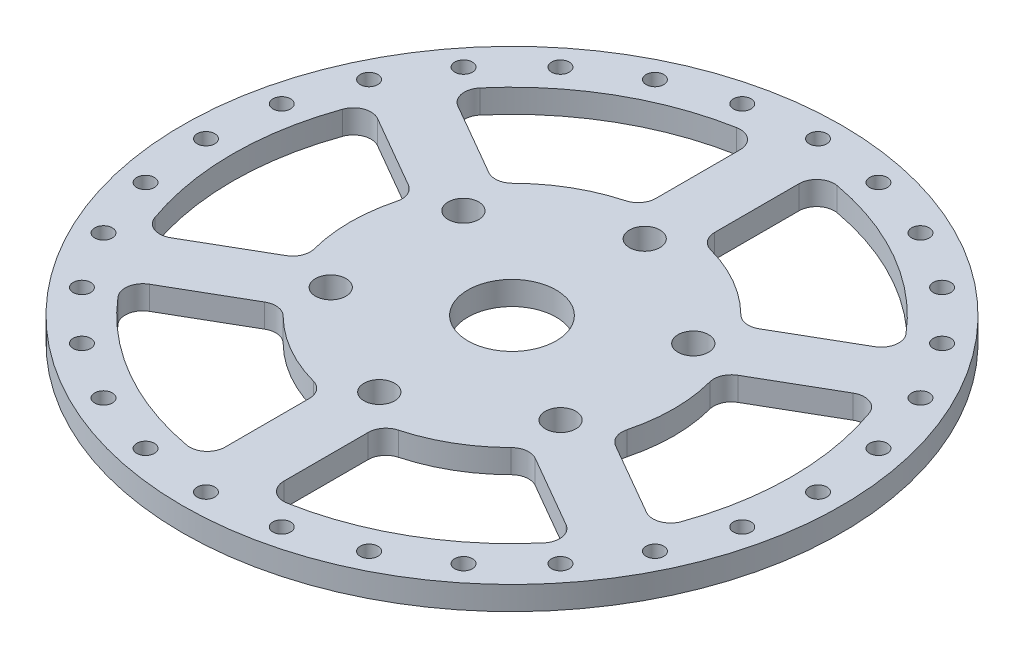
SolidWorks part; units mm, degrees
material "Thornel Mat VMA"
ref_plane "前视基准面" through (0, 0, 0) normal (0, 0, 1) x (1, 0, 0)
ref_plane "上视基准面" through (0, 0, 0) normal (0, 1, 0) x (1, 0, 0)
ref_plane "右视基准面" through (0, 0, 0) normal (1, 0, 0) x (0, 0, -1)
sketch "草图1" plane through (0, 0, 0) normal (0, 1, 0) x (1, 0, 0)
  line L0 (0, 27.5) -> (0, 47.5) construction
  line L1 (-5, 47.2361) -> (-5, 27.0416)
  line L2 (5, 47.2361) -> (5, 27.0416)
  line L3 (38.4077, 27.9482) -> (20.9187, 17.8509)
  line L4 (43.4077, 19.2879) -> (25.9187, 9.1907)
  line L5 (43.4077, -19.2879) -> (25.9187, -9.1907)
  line L6 (38.4077, -27.9482) -> (20.9187, -17.8509)
  line L7 (5, -47.2361) -> (5, -27.0416)
  line L8 (-5, -47.2361) -> (-5, -27.0416)
  line L9 (-38.4077, -27.9482) -> (-20.9187, -17.8509)
  line L10 (-43.4077, -19.2879) -> (-25.9187, -9.1907)
  line L11 (-43.4077, 19.2879) -> (-25.9187, 9.1907)
  line L12 (-38.4077, 27.9482) -> (-20.9187, 17.8509)
  circle A0 centre (0, 0) radius 56
  circle A1 centre (0, 0) radius 52 construction
  circle A2 centre (0, 0) radius 47.5
  circle A3 centre (0, 52) radius 1.5
  circle A4 centre (11.5711, 50.6963) radius 1.5
  circle A5 centre (22.562, 46.8504) radius 1.5
  circle A6 centre (32.4215, 40.6552) radius 1.5
  circle A7 centre (40.6552, 32.4215) radius 1.5
  circle A8 centre (46.8504, 22.562) radius 1.5
  circle A9 centre (50.6963, 11.5711) radius 1.5
  circle A10 centre (52, 0) radius 1.5
  circle A11 centre (50.6963, -11.5711) radius 1.5
  circle A12 centre (46.8504, -22.562) radius 1.5
  circle A13 centre (40.6552, -32.4215) radius 1.5
  circle A14 centre (32.4215, -40.6552) radius 1.5
  circle A15 centre (22.562, -46.8504) radius 1.5
  circle A16 centre (11.5711, -50.6963) radius 1.5
  circle A17 centre (0, -52) radius 1.5
  circle A18 centre (-11.5711, -50.6963) radius 1.5
  circle A19 centre (-22.562, -46.8504) radius 1.5
  circle A20 centre (-32.4215, -40.6552) radius 1.5
  circle A21 centre (-40.6552, -32.4215) radius 1.5
  circle A22 centre (-46.8504, -22.562) radius 1.5
  circle A23 centre (-50.6963, -11.5711) radius 1.5
  circle A24 centre (-52, 0) radius 1.5
  circle A25 centre (-50.6963, 11.5711) radius 1.5
  circle A26 centre (-46.8504, 22.562) radius 1.5
  circle A27 centre (-40.6552, 32.4215) radius 1.5
  circle A28 centre (-32.4215, 40.6552) radius 1.5
  circle A29 centre (-22.562, 46.8504) radius 1.5
  circle A30 centre (-11.5711, 50.6963) radius 1.5
  circle A31 centre (0, 0) radius 22.55 construction
  circle A32 centre (0, 22.55) radius 2.6
  circle A33 centre (19.5289, 11.275) radius 2.6
  circle A34 centre (19.5289, -11.275) radius 2.6
  circle A35 centre (0, -22.55) radius 2.6
  circle A36 centre (-19.5289, -11.275) radius 2.6
  circle A37 centre (-19.5289, 11.275) radius 2.6
  circle A38 centre (0, 0) radius 17.5
  circle A39 centre (0, 0) radius 27.5
  point P63 (0, 0)
  point P77 (0, 0)
  point P106 (0, 0)
  dimension "D1" = 112
  dimension "D2" = 104
  dimension "D3" = 95
  dimension "D4" = 3
  dimension "D6" = 45.1
  dimension "D7" = 5.2
  dimension "D9" = 35
  dimension "D10" = 55
  dimension "D11" = 10
  dimension "D5" = 28
  dimension "D8" = 6
  dimension "D12" = 6
extrude "凸台-拉伸1" add sketch "草图1" along normal blind 4 contours A39 A38 A37 A36 A35 A34 A33 A32 | A39 L8 A2 L7 | A0 A30 A29 A28 A27 A26 A25 A24 A23 A22 A21 A20 A19 A18 A17 A16 A15 A14 A13 A12 A11 A10 A9 A8 A7 A6 | A39 L10 A2 L9 | A39 L12 A2 L11 | A39 L2 A2 L1 | A39 L4 A2 L3 | A39 L6 A2 L5
fillet "圆角1" radius 3 24 edges at (5, 2, 27.0416) (5, 2, 47.2361) (38.4077, 2, 27.9482) (20.9187, 2, 17.8509) (43.4077, 2, -19.2879) (25.9187, 2, -9.1907) (25.9187, 2, 9.1907) (43.4077, 2, 19.2879) (5, 2, -47.2361) (5, 2, -27.0416) (20.9187, 2, -17.8509) (38.4077, 2, -27.9482) (-38.4077, 2, -27.9482) (-20.9187, 2, -17.8509) (-5, 2, -47.2361) (-43.4077, 2, 19.2879) (-25.9187, 2, 9.1907) (-25.9187, 2, -9.1907) (-43.4077, 2, -19.2879) (-5, 2, 47.2361) (-5, 2, 27.0416) (-20.9187, 2, 17.8509) (-38.4077, 2, 27.9482) (-5, 2, -27.0416)
sketch "草图2" plane through (0, 4, 0) normal (0, 1, 0) x (1, 0, 0)
  circle A0 centre (0, 0) radius 7.5
  circle A1 centre (0, 0) radius 17.5 construction
  circle A2 centre (0, 0) radius 17.5
  dimension "D1" = 15
extrude "凸台-拉伸2" add sketch "草图2" against normal up to surface (4 mm away) up to face at (-17.6705, 0, 30.6062)
